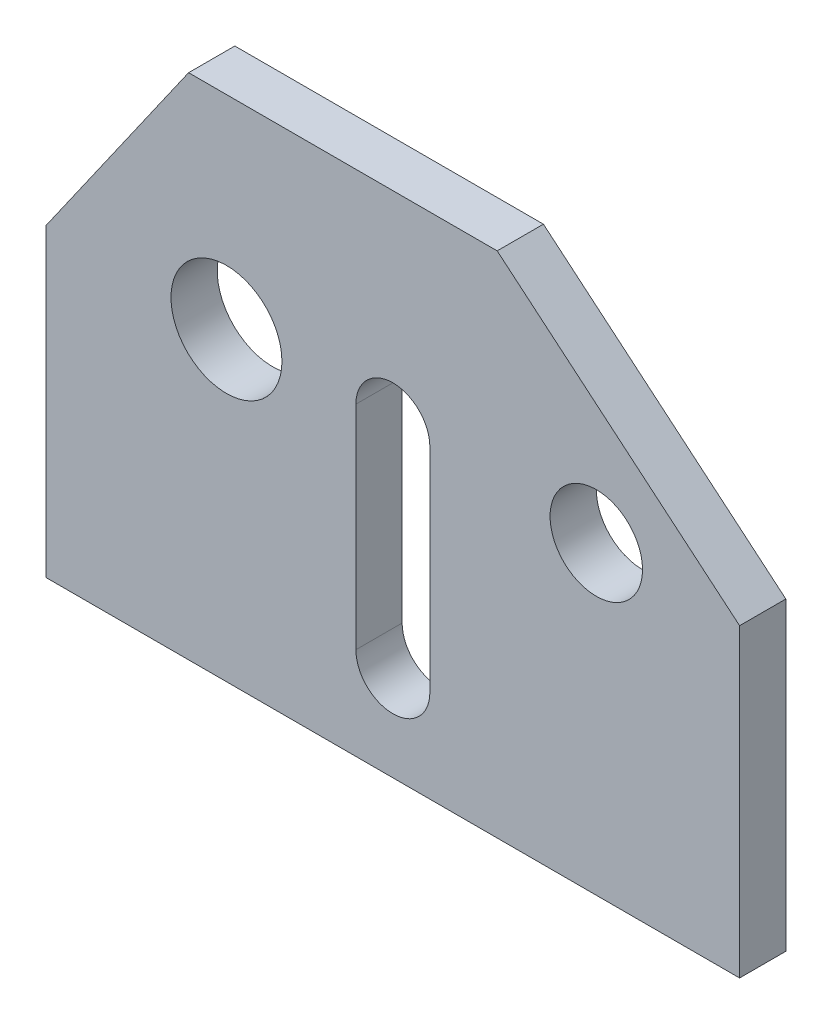
SolidWorks part; units mm, degrees
ref_plane "Front Plane" through (0, 0, 0) normal (0, 0, 1) x (1, 0, 0)
ref_plane "Top Plane" through (0, 0, 0) normal (0, 1, 0) x (1, 0, 0)
ref_plane "Right Plane" through (0, 0, 0) normal (1, 0, 0) x (0, 0, -1)
sketch "Sketch1" plane through (0, 0, 0) normal (0, 0, 1) x (1, 0, 0)
  line L0 (0, 0) -> (75, 0)
  line L1 (75, 0) -> (75, 33)
  line L2 (75, 33) -> (48.7814, 55)
  line L3 (48.7814, 55) -> (15.4046, 55)
  line L4 (15.4046, 55) -> (0, 33)
  line L5 (0, 33) -> (0, 0)
  line L6 (-14.2497, 33) -> (84.7878, 33) construction
  line L7 (37.5, 33) -> (37.5, 10) construction
  line L8 (41.5, 33) -> (41.5, 10)
  line L9 (33.5, 33) -> (33.5, 10)
  circle A0 centre (19.5, 33) radius 6
  circle A1 centre (59.5, 33) radius 5
  arc A2 (41.5, 33) -> (33.5, 33) centre (37.5, 33) ccw
  arc A3 (33.5, 10) -> (41.5, 10) centre (37.5, 10) ccw
  point P15 (37.5, 21.5)
  dimension "D7" = 12
  dimension "D8" = 4
  dimension "D12" = 10
  dimension "D1" = 75
  dimension "D2" = 33
  dimension "D3" = 0
  dimension "D4" = 35
  dimension "D5" = 50
  dimension "D6" = 55
  dimension "D9" = 23
  dimension "D10" = 18
  dimension "D11" = 22
  dimension "D13" = 37.5
extrude "Boss-Extrude1" add sketch "Sketch1" along normal blind 5
